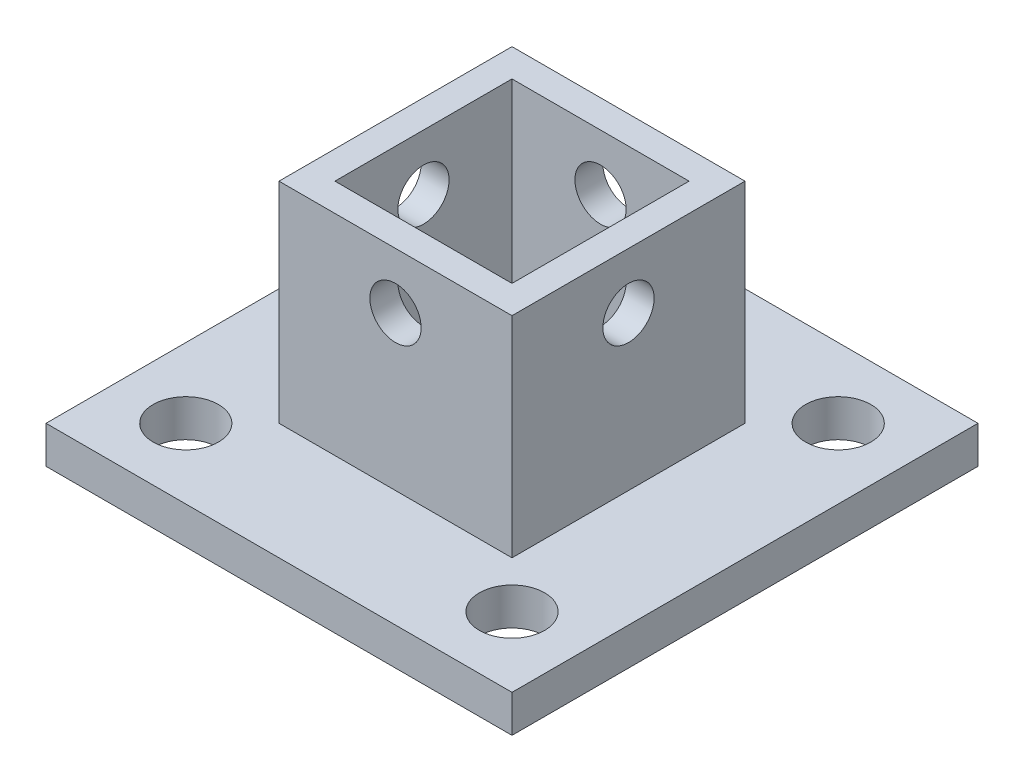
SolidWorks part; units mm, degrees
ref_plane "Front Plane" through (0, 0, 0) normal (0, 0, 1) x (1, 0, 0)
ref_plane "Top Plane" through (0, 0, 0) normal (0, 1, 0) x (1, 0, 0)
ref_plane "Right Plane" through (0, 0, 0) normal (1, 0, 0) x (0, 0, -1)
sketch "Sketch1" plane through (0, 0, 0) normal (0, 1, 0) x (1, 0, 0)
  line L1 (-25, 25) -> (25, 25)
  line L2 (-25, 25) -> (-25, -25)
  line L3 (-25, -25) -> (25, -25)
  line L4 (25, 25) -> (25, -25)
  line L5 (-55, 0) -> (55, 0) construction
  line L6 (0, -55) -> (0, 55) construction
  circle A0 centre (-17.5, 17.5) radius 3.5
  circle A1 centre (17.5, 17.5) radius 3.5
  circle A2 centre (17.5, -17.5) radius 3.5
  circle A3 centre (-17.5, -17.5) radius 3.5
  dimension "D5" = 7
  dimension "D1" = 50
  dimension "D2" = 50
  dimension "D3" = 25
  dimension "D4" = 25
  dimension "D8" = 35
  dimension "D9" = 17.5
  dimension "D10" = 17.5
  dimension "D6" = 2
  dimension "D7" = 2
extrude "Boss-Extrude1" add sketch "Sketch1" along normal blind 4 contours L4 L1 L2 L3 A3 A2 A1 A0
sketch "Sketch2" plane through (0, 4, 0) normal (0, 1, 0) x (1, 0, 0)
  line L0 (-25, 25) -> (-25, -25) construction
  line L1 (-12.5, 12.5) -> (12.5, 12.5)
  line L2 (-12.5, 12.5) -> (-12.5, -12.5)
  line L3 (-12.5, -12.5) -> (12.5, -12.5)
  line L4 (12.5, 12.5) -> (12.5, -12.5)
  line L5 (25, 25) -> (25, -25) construction
  line L6 (-25, 25) -> (25, 25) construction
  line L7 (-25, -25) -> (25, -25) construction
  line L9 (-9.5, 9.5) -> (9.5, 9.5)
  line L10 (-9.5, 9.5) -> (-9.5, -9.5)
  line L11 (-9.5, -9.5) -> (9.5, -9.5)
  line L12 (9.5, 9.5) -> (9.5, -9.5)
  dimension "D1" = 12.5
  dimension "D2" = 12.5
  dimension "D3" = 12.5
  dimension "D4" = 12.5
  dimension "D5" = 3
  dimension "D6" = 3
  dimension "D7" = 3
  dimension "D8" = 3
extrude "Boss-Extrude2" add sketch "Sketch2" along normal blind 22.5
sketch "Sketch3" plane through (-12.5, 0, 0) normal (-1, 0, 0) x (0, 0, 1)
  line L0 (0, -55) -> (0, 55) construction
  line L1 (-12.5, 26.5) -> (12.5, 26.5) construction
  circle A0 centre (0, 20.5) radius 2.75
  dimension "D1" = 5.5
  dimension "D2" = 6
extrude "Cut-Extrude1" cut sketch "Sketch3" against normal through all both and the other way through all
sketch "Sketch4" plane through (0, 0, 12.5) normal (0, 0, 1) x (1, 0, 0)
  line L0 (0, -55) -> (0, 55) construction
  line L1 (-12.5, 26.5) -> (12.5, 26.5) construction
  circle A0 centre (0, 20.5) radius 2.75
  dimension "D1" = 5.5
  dimension "D2" = 6
extrude "Cut-Extrude2" cut sketch "Sketch4" against normal through all both and the other way through all
